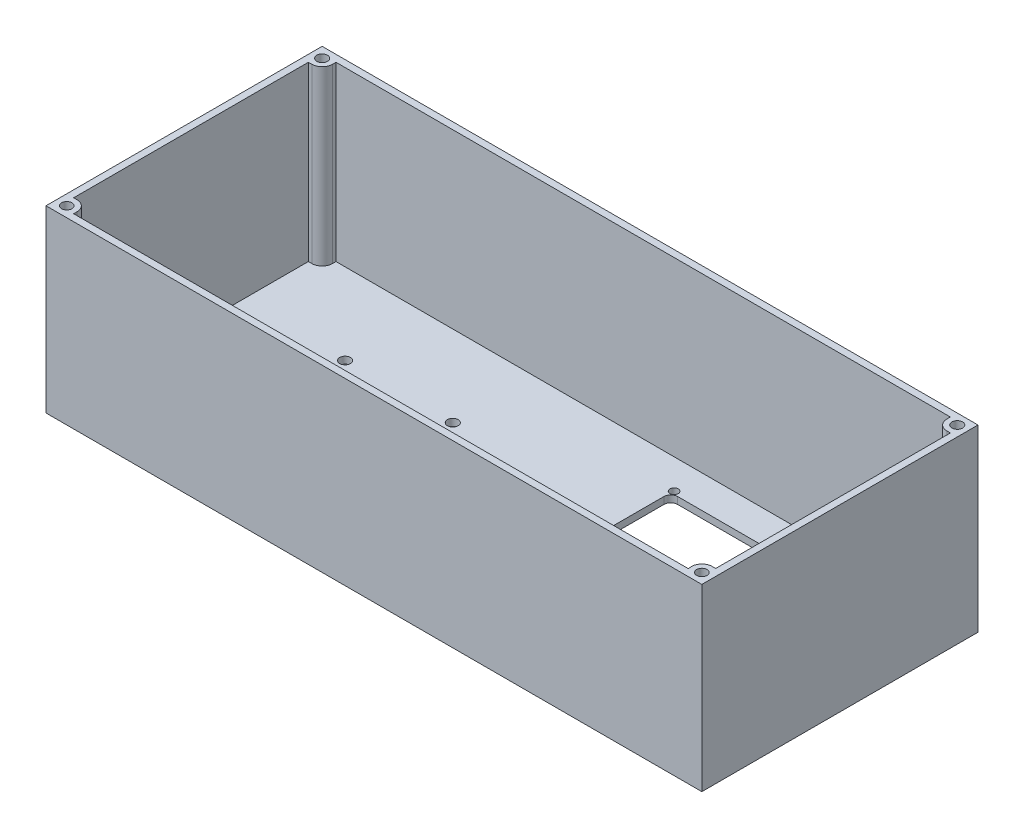
SolidWorks part; units mm, degrees
ref_plane "Front Plane" through (0, 0, 0) normal (0, 0, 1) x (1, 0, 0)
ref_plane "Top Plane" through (0, 0, 0) normal (0, 1, 0) x (1, 0, 0)
ref_plane "Right Plane" through (0, 0, 0) normal (1, 0, 0) x (0, 0, -1)
sketch "Sketch1" plane through (0, 0, 0) normal (0, 1, 0) x (1, 0, 0)
  line L1 (-87.4884, 53.0233) -> (102.5116, 53.0233)
  line L2 (-87.4884, 53.0233) -> (-87.4884, -26.9767)
  line L3 (-87.4884, -26.9767) -> (102.5116, -26.9767)
  line L4 (102.5116, 53.0233) -> (102.5116, -26.9767)
  dimension "D1" = 190
  dimension "D2" = 80
extrude "Boss-Extrude1" add sketch "Sketch1" along normal blind 2
sketch "Sketch2" plane through (0, 2, 0) normal (0, 1, 0) x (1, 0, 0)
  line L8 (-85.4884, 51.0233) -> (-85.4884, -24.9767)
  line L9 (100.5116, 51.0233) -> (-85.4884, 51.0233)
  line L10 (100.5116, -24.9767) -> (100.5116, 51.0233)
  line L11 (-85.4884, -24.9767) -> (100.5116, -24.9767)
  line L12 (-85.4884, 47.0233) -> (-85.4884, -20.9767)
  line L13 (96.5116, 51.0233) -> (-81.4884, 51.0233)
  line L16 (-84.4884, 47.0233) -> (-85.4884, 47.0233)
  line L17 (-81.4884, 50.0233) -> (-81.4884, 51.0233)
  line L18 (96.5116, 50.0233) -> (96.5116, 51.0233)
  line L19 (99.5116, 47.0233) -> (100.5116, 47.0233)
  line L20 (102.5116, -26.9767) -> (102.5116, 53.0233)
  line L21 (-87.4884, -26.9767) -> (102.5116, -26.9767)
  line L22 (-87.4884, 53.0233) -> (-87.4884, -26.9767)
  line L23 (102.5116, 53.0233) -> (-87.4884, 53.0233)
  line L24 (102.5116, -26.9767) -> (102.5116, 53.0233)
  line L25 (-87.4884, -26.9767) -> (102.5116, -26.9767)
  line L26 (-87.4884, 53.0233) -> (-87.4884, -26.9767)
  line L27 (102.5116, 53.0233) -> (-87.4884, 53.0233)
  line L28 (96.5116, -23.9767) -> (96.5116, -24.9767)
  line L29 (99.5116, -20.9767) -> (100.5116, -20.9767)
  line L30 (100.5116, -20.9767) -> (100.5116, 47.0233)
  line L31 (-84.4884, -20.9767) -> (-85.4884, -20.9767)
  line L32 (-81.4884, -23.9767) -> (-81.4884, -24.9767)
  line L33 (-81.4884, -24.9767) -> (96.6832, -24.9767)
  arc A0 (-84.4884, 47.0233) -> (-81.4884, 50.0233) centre (-84.4884, 50.0233) ccw
  circle A1 centre (-84.4884, 50.0233) radius 1.55
  arc A2 (96.5116, 50.0233) -> (99.5116, 47.0233) centre (99.5116, 50.0233) ccw
  arc A3 (99.5116, -20.9767) -> (96.6832, -24.9767) centre (99.5116, -23.9767) ccw
  circle A5 centre (99.5116, 50.0233) radius 1.55
  circle A6 centre (99.5116, -23.9767) radius 1.5
  circle A7 centre (-84.4884, -23.9767) radius 1.5
  arc A8 (-81.4884, -23.9767) -> (-84.4884, -20.9767) centre (-84.4884, -23.9767) ccw
  line M23 (-87.4884, 53.0233) -> (-87.4884, -26.9767)
  line M24 (-87.4884, -26.9767) -> (102.5116, -26.9767)
  line M25 (102.5116, -26.9767) -> (102.5116, 53.0233)
  line M26 (102.5116, 53.0233) -> (-87.4884, 53.0233)
  dimension "D3" = 6
  dimension "D4" = 3.1
  dimension "D7" = 6
  dimension "D8" = 3.1
  dimension "D11" = 3
  dimension "D14" = 3
  dimension "D5" = 3
  dimension "D6" = 3
  dimension "D9" = 3
  dimension "D10" = 3
  dimension "D12" = 3
  dimension "D13" = 3
  dimension "D15" = 3
  dimension "D16" = 3
  dimension "D1" = 2
  dimension "D2" = 0
extrude "Boss-Extrude2" add sketch "Sketch2" along normal blind 50 contours A7 A6 A5 A1 L32 A8 L31 L12 L16 A0 L17 L13 L18 A2 L19 L30 L29 A3 L33 M26 M23 M24 M25
sketch "Sketch3" plane through (0, 0, 0) normal (0, -1, 0) x (1, 0, 0)
  line L1 (26.9616, 15.5267) -> (83.0616, 15.5267)
  line L2 (24.9616, 13.5267) -> (24.9616, -39.5733)
  line L3 (26.9616, -41.5733) -> (83.0616, -41.5733)
  line L4 (85.0616, 13.5267) -> (85.0616, -39.5733)
  line L5 (129.3132, -13.0233) -> (-145.0579, -13.0233) construction
  line L6 (-87.4884, 26.9767) -> (102.5116, 26.9767) construction
  line L7 (102.5116, -53.0233) -> (-87.4884, -53.0233) construction
  line L8 (55.0116, 33.2529) -> (55.0116, -49.9951) construction
  line L9 (22.5116, 18.9767) -> (87.5116, 18.9767) construction
  line L10 (22.5116, 18.9767) -> (22.5116, -45.0233) construction
  line L11 (22.5116, -45.0233) -> (87.5116, -45.0233) construction
  line L12 (87.5116, 18.9767) -> (87.5116, -45.0233) construction
  line L13 (102.5116, 26.9767) -> (102.5116, -53.0233) construction
  line L14 (-39.7384, 17.5235) -> (-39.7384, -43.9134) construction
  line L15 (-56.7884, -1.4933) -> (-22.6884, -1.4933)
  line L16 (-56.7884, -1.4933) -> (-56.7884, -24.5933)
  line L17 (-56.7884, -24.5933) -> (-22.6884, -24.5933)
  line L18 (-22.6884, -1.4933) -> (-22.6884, -24.5933)
  line L19 (-57.4884, 3.7767) -> (-21.9884, 3.7767) construction
  line L20 (-57.4884, 3.7767) -> (-57.4884, -29.8233) construction
  line L21 (-57.4884, -29.8233) -> (-21.9884, -29.8233) construction
  line L22 (-21.9884, 3.7767) -> (-21.9884, -29.8233) construction
  line L23 (-87.4884, -53.0233) -> (-87.4884, 26.9767) construction
  arc A0 (26.9616, 15.5267) -> (24.9616, 13.5267) centre (26.9616, 13.5267) ccw
  arc A1 (85.0616, 13.5267) -> (83.0616, 15.5267) centre (83.0616, 13.5267) ccw
  arc A2 (24.9616, -39.5733) -> (26.9616, -41.5733) centre (26.9616, -39.5733) ccw
  arc A3 (83.0616, -41.5733) -> (85.0616, -39.5733) centre (83.0616, -39.5733) ccw
  circle A4 centre (25.1116, 16.3267) radius 1.2
  circle A5 centre (84.9116, 16.3267) radius 1.2
  circle A6 centre (25.1116, -42.3733) radius 1.2
  circle A7 centre (84.9116, -42.3733) radius 1.2
  circle A8 centre (-55.3384, 1.7767) radius 1.55
  circle A9 centre (-24.1384, 1.7767) radius 1.55
  circle A10 centre (-55.3384, -27.5233) radius 1.55
  circle A11 centre (-24.1384, -27.5233) radius 1.55
  dimension "D3" = 4
  dimension "D6" = 2.4
  dimension "D14" = 3.1
  dimension "D1" = 60.1
  dimension "D2" = 57.1
  dimension "D4" = 64
  dimension "D5" = 65
  dimension "D7" = 59.8
  dimension "D8" = 58.7
  dimension "D9" = 15
  dimension "D10" = 23.1
  dimension "D11" = 34.1
  dimension "D12" = 35.5
  dimension "D13" = 33.6
  dimension "D15" = 2
  dimension "D16" = 2.15
  dimension "D17" = 2.3
  dimension "D18" = 2.15
  dimension "D19" = 2.15
  dimension "D20" = 2
  dimension "D21" = 2.15
  dimension "D22" = 2.3
  dimension "D23" = 5.27
  dimension "D24" = 30
extrude "Cut-Extrude1" cut sketch "Sketch3" against normal through all
